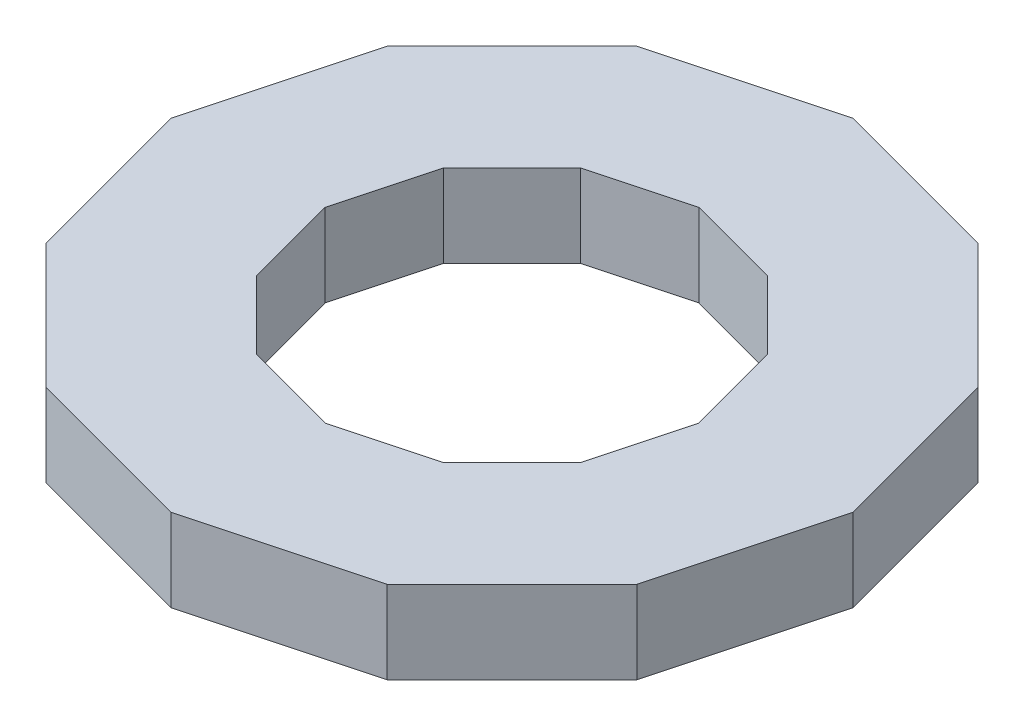
SolidWorks part; units mm, degrees
ref_plane "Front Plane" through (0, 0, 0) normal (0, 0, 1) x (1, 0, 0)
ref_plane "Top Plane" through (0, 0, 0) normal (0, 1, 0) x (1, 0, 0)
ref_plane "Right Plane" through (0, 0, 0) normal (1, 0, 0) x (0, 0, -1)
sketch "Sketch1" plane through (0, 0, 0) normal (0, 1, 0) x (1, 0, 0)
  line L0 (0, 0) -> (43.0108, 0) construction
  line L1 (43.0108, 0) -> (37.2485, 21.5054)
  line L2 (37.2485, 21.5054) -> (21.5054, 37.2485)
  line L3 (21.5054, 37.2485) -> (0, 43.0108)
  line L4 (0, 43.0108) -> (-21.5054, 37.2485)
  line L5 (-21.5054, 37.2485) -> (-37.2485, 21.5054)
  line L6 (-37.2485, 21.5054) -> (-43.0108, 0)
  line L7 (-43.0108, 0) -> (-37.2485, -21.5054)
  line L8 (-37.2485, -21.5054) -> (-21.5054, -37.2485)
  line L9 (-21.5054, -37.2485) -> (0, -43.0108)
  line L10 (0, -43.0108) -> (21.5054, -37.2485)
  line L11 (21.5054, -37.2485) -> (37.2485, -21.5054)
  line L12 (37.2485, -21.5054) -> (43.0108, 0)
  line L13 (78.5105, 0) -> (67.992, 39.2552)
  line L14 (67.992, 39.2552) -> (39.2552, 67.992)
  line L15 (39.2552, 67.992) -> (0, 78.5105)
  line L16 (0, 78.5105) -> (-39.2552, 67.992)
  line L17 (-39.2552, 67.992) -> (-67.992, 39.2552)
  line L18 (-67.992, 39.2552) -> (-78.5105, 0)
  line L19 (-78.5105, 0) -> (-67.992, -39.2552)
  line L20 (-67.992, -39.2552) -> (-39.2552, -67.992)
  line L21 (-39.2552, -67.992) -> (0, -78.5105)
  line L22 (0, -78.5105) -> (39.2552, -67.992)
  line L23 (39.2552, -67.992) -> (67.992, -39.2552)
  line L24 (67.992, -39.2552) -> (78.5105, 0)
  circle A0 centre (0, 0) radius 41.5453 construction
  circle A1 centre (0, 0) radius 75.8353 construction
  dimension "D1" = 34.29
  dimension "D2" = 40.64
extrude "Boss-Extrude1" add sketch "Sketch1" along normal blind 19.05
